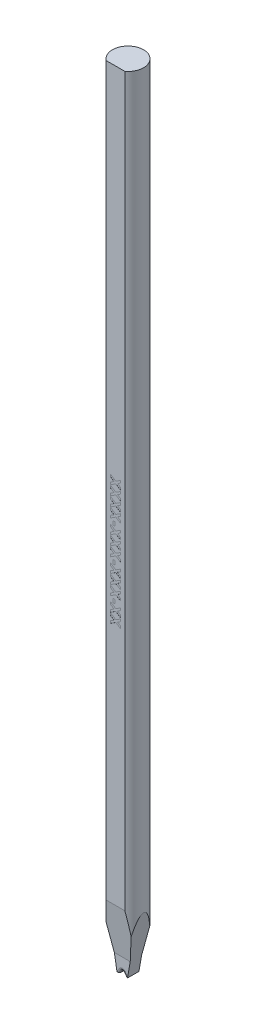
SolidWorks part; units mm, degrees
ref_plane "Ebene vorne" through (0, 0, 0) normal (0, 0, 1) x (1, 0, 0)
ref_plane "Ebene oben" through (0, 0, 0) normal (0, 1, 0) x (1, 0, 0)
ref_plane "Ebene rechts" through (0, 0, 0) normal (1, 0, 0) x (0, 0, -1)
sketch "sketch_TL_cutting" plane through (0, 0, 0) normal (0, 1, 0) x (1, 0, 0)
  circle A0 centre (0, 0) radius 1.4986
extrude "TL_cutting" add sketch "sketch_TL_cutting" along normal blind 75.9968
sketch "sketch_TDF_grinding" plane through (0, 0, 0) normal (0, 1, 0) x (1, 0, 0)
  line L0 (0, 0) -> (0, -1.2014) construction
  line L1 (-1.5086, -4.2186) -> (1.5086, -4.2186)
  line L2 (-1.5086, -4.2186) -> (-1.5086, -1.2014)
  line L3 (-1.5086, -1.2014) -> (1.5086, -1.2014)
  line L4 (1.5086, -4.2186) -> (1.5086, -1.2014)
  circle A1 centre (0, 0) radius 1.4986 construction
  point P9 (0, -4.2186)
  dimension "TD_2Offset_X" = 3.0172
  dimension "TD_2Offset_Z" = 3.0172
extrude "TDF_grinding" cut sketch "sketch_TDF_grinding" along normal through all
sketch "sketch_engraving" plane through (0, 0, 1.2014) normal (0, 0, 1) x (1, 0, 0)
  line L0 (0.8958, 75.9968) -> (-0.8958, 75.9968) construction
  line L6 (-0.8958, 0) -> (0.8958, 0) construction
  line L7 (0, 0) -> (0, 41.7982) construction
  line L8 (-0.5, 41.7982) -> (-0.5, 0) construction
  text T0 "XXXX-XXX-XXX-XX" font "Arial" height 1
  dimension "D2" = 0.5
  dimension "EngravingStart" = 34.1986
extrude "engraving" cut sketch "sketch_engraving" against normal blind 0.005
sketch "sketch_VW_VR_grinding" plane through (0, 0, 0) normal (0, 0, 1) x (1, 0, 0)
  line L0 (-1.4936, -0.01) -> (-1.4936, 1.4836)
  line L1 (1.4936, -0.01) -> (1.4936, 1.4836)
  line L2 (-1.4936, 0) -> (1.4936, 0) construction
  line L3 (-1.5086, 1.4886) -> (-1.4986, 1.4886)
  line L4 (1.4986, 1.4886) -> (1.5086, 1.4886)
  line L5 (-1.5086, 1.4886) -> (-1.5086, -0.01)
  line L6 (-1.5086, -0.01) -> (-1.4936, -0.01)
  line L7 (1.4936, -0.01) -> (1.5086, -0.01)
  line L8 (1.5086, -0.01) -> (1.5086, 1.4886)
  line L9 (-1.4986, 1.4886) -> (-1.4986, 1.4836) construction
  line L10 (-1.4936, 1.4836) -> (-1.4986, 1.4836) construction
  line L11 (1.4936, 1.4836) -> (1.4986, 1.4836) construction
  line L12 (1.4986, 1.4886) -> (1.4986, 1.4836) construction
  arc A0 (-1.4986, 1.4886) -> (-1.4936, 1.4836) centre (-1.4986, 1.4836) cw
  arc A2 (1.4936, 1.4836) -> (1.4986, 1.4886) centre (1.4986, 1.4836) cw
  dimension "D1" = 0.01
  dimension "D4" = 3.0172
extrude "VW_VR_grinding" cut sketch "sketch_VW_VR_grinding" against normal blind 1.5086 and the other way blind 1.5086
sketch "sketch_ISA_grinding" plane through (0, 0, 0) normal (0, 0, 1) x (1, 0, 0)
  line L0 (-0.5004, 0) -> (-1.5086, 5.7179)
  line L4 (1.5086, 5.7179) -> (0.5004, 0)
  line L5 (0.5004, 0) -> (-0.5004, 0)
  line L6 (0, 0) -> (0, 30.49) construction
  line L7 (-1.5086, 5.7179) -> (-1.5086, -0.01)
  line L12 (-1.5086, -0.01) -> (1.5086, -0.01)
  line L13 (1.5086, -0.01) -> (1.5086, 5.7179)
  dimension "ISA" = 20
  dimension "TD_2Offset" = 3.0172
  dimension "Offset" = 0.01
extrude "ISA_grinding" cut sketch "sketch_ISA_grinding" against normal blind 1.5086 and the other way blind 1.5086
sketch "sketch_pre_FRX_BRX" plane through (0, 0, 0) normal (1, 0, 0) x (0, 0, -1)
  line L0 (1.4986, -0.01) -> (1.4986, 3.9152) construction
  line L1 (-1.2014, -0.01) -> (-1.2014, 1.4886) construction
  line L2 (-0.5512, -0.01) -> (-0.5512, 1.4886)
  line L3 (-0.5512, 1.4886) -> (-1.5086, 1.4886)
  line L4 (-1.5086, 1.4886) -> (-1.5086, -0.01)
  line L5 (-1.5086, -0.01) -> (-0.5512, -0.01)
  line L6 (0.5486, -0.01) -> (0.5486, 1.4886)
  line L7 (0.5486, 1.4886) -> (1.5086, 1.4886)
  line L8 (1.5086, 1.4886) -> (1.5086, -0.01)
  line L9 (1.5086, -0.01) -> (0.5486, -0.01)
  dimension "D3" = 0.01
  dimension "D4" = 1.4986
  dimension "D5" = 3.0172
  dimension "D6" = 1.0998
  dimension "D2" = 0.01
  dimension "D7" = 2.0498
extrude "pre_FRX_BRX" cut sketch "sketch_pre_FRX_BRX" against normal blind 1.5086 and the other way blind 1.5086
sketch "sketch_contour_V-Groove" plane through (0, 0, 0) normal (1, 0, 0) x (0, 0, -1)
  line L0 (-1.2014, 0.32) -> (-0.0013, 0.32)
  line L1 (-0.0013, 0.32) -> (1.4986, 0.32)
  line L2 (1.4986, -0.8411) -> (1.4986, 1.3178) construction
  line L3 (-1.2014, -0.9209) -> (-1.2014, 1.9363) construction
  line L4 (-1.2014, 0) -> (1.4986, 0) construction
  line L5 (0.5486, 0) -> (0.5486, 0.32) construction
  line L6 (-0.5512, 0) -> (-0.5512, 0.32) construction
  dimension "D1" = 0
ref_plane "front" through (0, 0, 1.2014) normal (0, 0, 1) x (1, 0, 0)
ref_plane "back" through (0, 0, -1.4986) normal (0, 0, 1) x (1, 0, 0)
sketch "sketch_section_V-Groove" plane through (0, 0, 1.2014) normal (0, 0, 1) x (1, 0, 0)
  line L0 (-2.5165, -3.2004) -> (-0.081, 0.2779)
  line L2 (0.081, 0.2779) -> (2.5165, -3.2004)
  line L3 (-2.5165, -3.2004) -> (2.5165, -3.2004)
  line L4 (0, -3.2004) -> (0, 0.32) construction
  line L5 (-0.2756, 0) -> (0.2756, 0) construction
  arc A0 (0.081, 0.2779) -> (-0.081, 0.2779) centre (0, 0.2211) ccw
  dimension "GA" = 70
sweep "V-Groove_EDM" cut profiles "sketch_section_V-Groove" path "sketch_contour_V-Groove"
fillet "FR_EDM" radius 0.2489 3 edges at (0.1783, 0.1389, 0.5512) (0, 0.32, 0.5512) (-0.1783, 0.1389, 0.5512)
fillet "BR_EDM" radius 0.2489 3 edges at (0.1783, 0.1389, -0.5486) (0, 0.32, -0.5486) (-0.1783, 0.1389, -0.5486)
sketch "sketch_FA_BA_grinding" plane through (0, 0, 0) normal (1, 0, 0) x (0, 0, -1)
  line L2 (2.4986, 15.3733) -> (2.4986, -0.1)
  line L3 (2.4986, -0.1) -> (0.5486, -0.1)
  line L5 (0.5486, -0.1) -> (0.5486, 1.4986)
  line L6 (0.5486, 1.4986) -> (2.4986, 15.3733)
  line L7 (1.4986, -0.1) -> (1.4986, 8.2579) construction
  line L8 (-1.2014, 6.1253) -> (-1.2014, -0.1) construction
  line L9 (-3.4989, 22.4726) -> (-0.5512, 1.4986)
  line L10 (-0.5512, 1.4986) -> (-0.5512, -0.1)
  line L11 (-0.5512, -0.1) -> (-3.4989, -0.1)
  line L12 (-3.4989, -0.1) -> (-3.4989, 22.4726)
  line L13 (-0.5512, 1.4986) -> (0.5486, 1.4986) construction
  dimension "D4" = 1
  dimension "D1" = 0.1
  dimension "FA" = 8
  dimension "BA" = 8
extrude "FA_BA_grinding" cut sketch "sketch_FA_BA_grinding" against normal blind 1.5086 and the other way blind 1.5086
sketch "sketch_groove_dimensions" plane through (0, 0, 0) normal (1, 0, 0) x (0, 0, -1)
  line L0 (-0.3023, 0.32) -> (0.2997, 0.32)
  line L1 (-0.5512, 0) -> (-0.5512, 0.569) construction
  line L2 (1.4986, 0) -> (1.4986, 0.4166) construction
  line L3 (0.5486, 0) -> (0.5486, 0.569) construction
  line L4 (-1.2014, 0) -> (-1.2014, 0.3999) construction
  arc A0 (0.2997, 0.32) -> (0.5486, 0.569) centre (0.2997, 0.569) ccw
  arc A1 (-0.3023, 0.32) -> (-0.5512, 0.569) centre (-0.3023, 0.569) cw
equation "\"_Offset\"=0.01mm"
equation "\"TL\"=75.9968mm"
equation "\"TD\"=2.9972mm"
equation "\"TDF\"=2.70002mm"
equation "\"BA\"=8deg"
equation "\"ISA\"=20deg"
equation "\"FA\"=8deg"
equation "\"GR\"=0.09906mm"
equation "\"GA\"=70deg"
equation "\"GD\"=0.32004mm"
equation "\"FL\"=1.09982mm"
equation "\"F\"=0.59944mm"
equation "\"FX\"=0.65024mm"
equation "\"B\"=0.55118mm"
equation "\"VW\"=0mm"
equation "\"cleaned_VR\"= IIF ( \"VR\" > 0 , \"VR\" , \"E\" - \"_Offset\" )"
equation "\"cleaned_VW\"= IIF ( \"VW\" > 0 , \"VW\" , \"TD\" - \"_Offset\" )"
equation "\"back_edge\"= \"TD\" / 2 - \"X\""
equation "\"side_edge_Offset\"= \"TD\" / 2 + \"_Offset\""
equation "\"TD@sketch_TL_cutting\"=\"TD\""
equation "\"TL@TL_cutting\"=\"TL\""
equation "\"TDF@sketch_TDF_grinding\"=\"TDF\""
equation "\"TD_2Offset_X@sketch_TDF_grinding\"=\"TD\"+2*\"_Offset\""
equation "\"TD_2Offset_Z@sketch_TDF_grinding\"=\"TD\"+2*\"_Offset\""
equation "\"TL_Offset\"= \"TL\" + \"_Offset\""
equation "\"ISA@sketch_ISA_grinding\"=\"ISA\""
equation "\"W@sketch_ISA_grinding\"=\"W\""
equation "\"TD_2Offset@sketch_ISA_grinding\"=\"TD\"+2*\"_Offset\""
equation "\"Offset@sketch_ISA_grinding\"=\"_Offset\""
equation "\"05TD_Offset_posZ@ISA_grinding\"=\"side_edge_Offset\""
equation "\"05TD_Offset_negZ@ISA_grinding\"=\"side_edge_Offset\""
equation "\"E\"=1.4986mm"
equation "\"cleaned_X\"= IIF ( \"X\" > 0 , \"X\" , \"TD\" / 2 - \"FL\" / 2 )"
equation "\"FR\"=0.24892mm"
equation "\"BR\"=0.24892mm"
equation "\"D1\"= \"side_edge_Offset\""
equation "\"D2\"= \"side_edge_Offset\""
equation "\"TDF@sketch_FA_BA_grinding\" = \"TDF\""
equation "\"FL@sketch_FA_BA_grinding\"=\"FL\""
equation "\"E@sketch_FA_BA_grinding\" = \"E\""
equation "\"D1@FA_BA_grinding\"=\"side_edge_Offset\""
equation "\"D2@FA_BA_grinding\"=\"side_angle_Offset\""
equation "\"10GD@sketch_section_V-Groove\" = 10 * \"GD\""
equation "\"GA@sketch_section_V-Groove\" = \"GA\""
equation "\"GD@sketch_section_V-Groove\" = \"GD\""
equation "\"B@sketch_section_V-Groove\" = \"B\""
equation "\"GD@sketch_contour_V-Groove\" = \"GD\""
equation "\"cleaned_FRX\"= IIF ( \"FRX\" > 0 , \"FRX\" , \"FR\" )"
equation "\"cleaned_BRX\"= IIF ( \"BRX\" > 0 , \"BRX\" , \"BR\" )"
equation "\"FL_groove_angle\"=0deg"
equation "\"D3@sketch_pre_FRX_BRX\" = \"_Offset\""
equation "\"D4@sketch_pre_FRX_BRX\" = \"E\""
equation "\"D5@sketch_pre_FRX_BRX\" = 2 * \"side_edge_Offset\""
equation "\"D6@sketch_pre_FRX_BRX\" = \"FL\" + ( \"FR\" - \"cleaned_FRX\" ) + ( \"BR\" - \"cleaned_BRX\" )"
equation "\"TD/2@sketch_pre_FRX_BRX\" = \"TD\" / 2"
equation "\"TDF@sketch_pre_FRX_BRX\" = \"TDF\""
equation "\"D2@sketch_pre_FRX_BRX\" = \"_Offset\""
equation "\"D1@pre_FRX_BRX\" = \"side_edge_Offset\""
equation "\"D2@pre_FRX_BRX\" = \"side_edge_Offset\""
equation "\"D1@BR_EDM\"=\"BR\""
equation "\"TD/2@sketch_FA_BA_grinding\" = \"TD\" / 2"
equation "\"TD/2@sketch_contour_V-Groove\" = \"TD\" / 2"
equation "\"TDF@sketch_contour_V-Groove\" = \"TDF\""
equation "\"D1@sketch_contour_V-Groove\"=\"FL_groove_angle\""
equation "\"FL@sketch_contour_V-Groove\"=\"FL\""
equation "\"FL/2@sketch_contour_V-Groove\" = \"FL\" / 2"
equation "\"D1@FR_EDM\"=\"FR\""
equation "\"D1@sketch_VW_VR_grinding\" = \"_Offset\""
equation "\"D4@sketch_VW_VR_grinding\" = 2 * \"side_edge_Offset\""
equation "\"VR@sketch_VW_VR_grinding\" = \"cleaned_VR\""
equation "\"VW@sketch_VW_VR_grinding\"=\"cleaned_VW\""
equation "\"D1@VW_VR_grinding\" = \"side_edge_Offset\""
equation "\"D2@VW_VR_grinding\" = \"side_edge_Offset\""
equation "\"X\"=0mm"
equation "\"VR\"=0mm"
equation "\"W\"=1.00076mm"
equation "\"VW_radius\"= \"cleaned_VW\" / 10"
equation "\"VW_radius_cleaned\"= IIF ( \"VW\" > 0 , \"VW_radius\" , \"_Offset\" / 2 )"
equation "\"D2@sketch_VW_VR_grinding\"=\"VW_radius_cleaned\""
equation "\"FRX\"=0mm"
equation "\"BRX\"=0mm"
equation "\"FA@sketch_FA_BA_grinding\" = \"FA\""
equation "\"D4@sketch_FA_BA_grinding\"=\"_Offset\"*100"
equation "\"BA@sketch_FA_BA_grinding\" = \"BA\""
equation "\"D1@sketch_groove_dimensions\" = \"TD\" / 2"
equation "\"FL@sketch_groove_dimensions\" = \"FL\""
equation "\"FR@sketch_groove_dimensions\" = \"FR\""
equation "\"BR@sketch_groove_dimensions\" = \"BR\""
equation "\"FRX@sketch_groove_dimensions\" = \"cleaned_FRX\""
equation "\"BRX@sketch_groove_dimensions\" = \"cleaned_BRX\""
equation "\"GD@sketch_groove_dimensions\" = \"GD\""
equation "\"cleaned_FX\"= IIF ( \"FX\" > 0 , \"FX\" , \"TDF\" - ( \"TD\" + \"FL\" ) / 2 )"
equation "\"D7@sketch_pre_FRX_BRX\"=\"TDF\"-\"cleaned_FX\"-(\"FR\"-\"cleaned_FRX\")"
equation "\"FX@sketch_contour_V-Groove\" = \"cleaned_FX\""
equation "\"FX@sketch_FA_BA_grinding\" = \"cleaned_FX\""
equation "\"TDF@sketch_groove_dimensions\" = \"TDF\""
equation "\"FX@sketch_groove_dimensions\" = \"cleaned_FX\""
equation "\"EngravingStart\" = \"TL\" * 0.45"
equation "\"EngravingStart@sketch_engraving\" = \"EngravingStart\""
